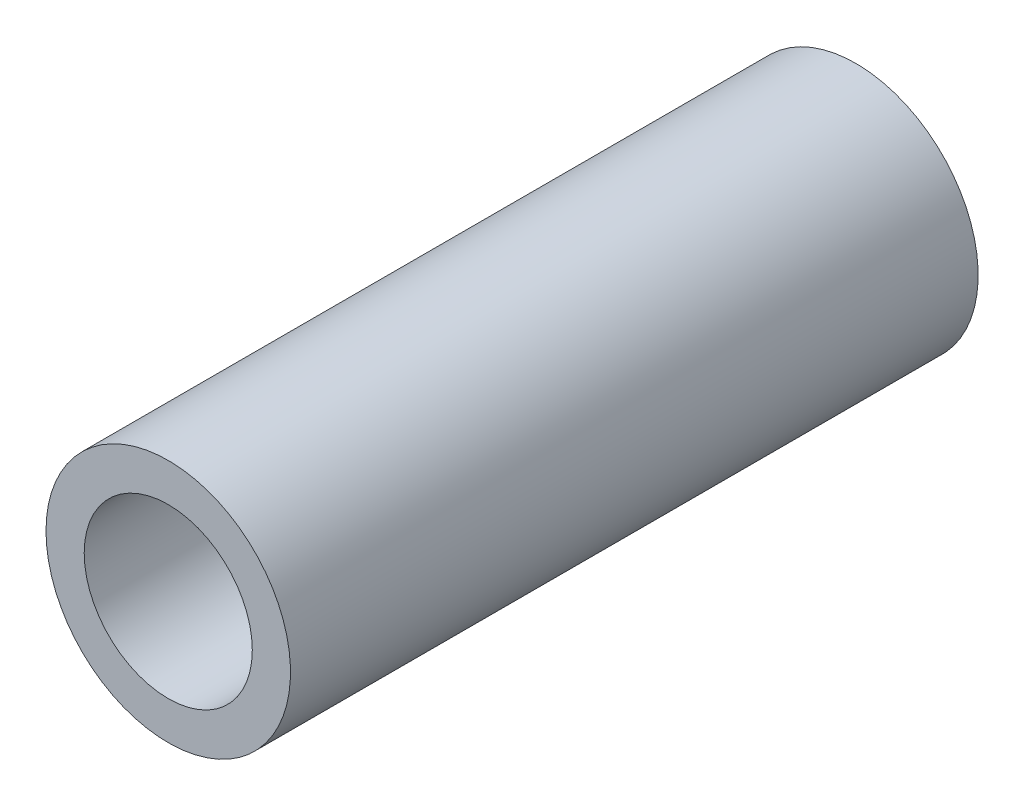
SolidWorks part; units mm, degrees
ref_plane "Plan de face" through (0, 0, 0) normal (0, 0, 1) x (1, 0, 0)
ref_plane "Plan de dessus" through (0, 0, 0) normal (0, 1, 0) x (1, 0, 0)
ref_plane "Plan de droite" through (0, 0, 0) normal (1, 0, 0) x (0, 0, -1)
sketch "Esquisse1" plane through (0, 0, 0) normal (0, 0, 1) x (1, 0, 0)
  circle A0 centre (0, 0) radius 2
  circle A1 centre (0, 0) radius 1.375
  dimension "D1" = 4
  dimension "D2" = 2.75
extrude "Boss.-Extru.1" add sketch "Esquisse1" along normal blind 11.25
